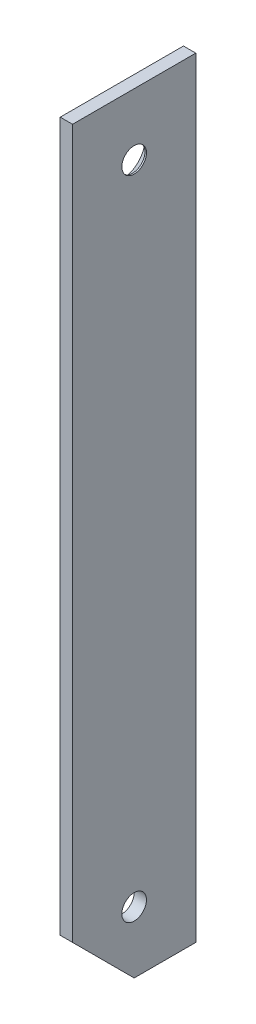
SolidWorks part; units mm, degrees
ref_plane "Front Plane" through (0, 0, 0) normal (0, 0, 1) x (1, 0, 0)
ref_plane "Top Plane" through (0, 0, 0) normal (0, 1, 0) x (1, 0, 0)
ref_plane "Right Plane" through (0, 0, 0) normal (1, 0, 0) x (0, 0, -1)
sketch "Sketch1" plane through (0, 0, 0) normal (1, 0, 0) x (0, 0, -1)
  line L0 (0, 125) -> (0, -125) construction
  line L1 (-20, 125) -> (20, 125)
  line L2 (-20, 125) -> (-20, -125)
  line L3 (-20, -125) -> (20, -125)
  line L4 (20, 125) -> (20, -125)
  line L5 (-20, 125) -> (20, -125) construction
  line L6 (-20, -125) -> (20, 125) construction
  line L7 (0, 0) -> (45.6121, 0) construction
  circle A0 centre (0, 105) radius 4
  circle A1 centre (0, -105) radius 4
  point P0 (0, 0)
  dimension "D3" = 20
  dimension "D1" = 125
  dimension "D2" = 40
  dimension "D4" = 125
  dimension "D6" = 20
  dimension "D7" = 20
  dimension "D8" = 20
extrude "Boss-Extrude1" add sketch "Sketch1" along normal blind 4
chamfer "Chamfer1" distance 3.5 angle 45 1 edges at (0, 105, -4)
chamfer "Chamfer3" distance 20 angle 45 1 edges at (2, -125, 20)
